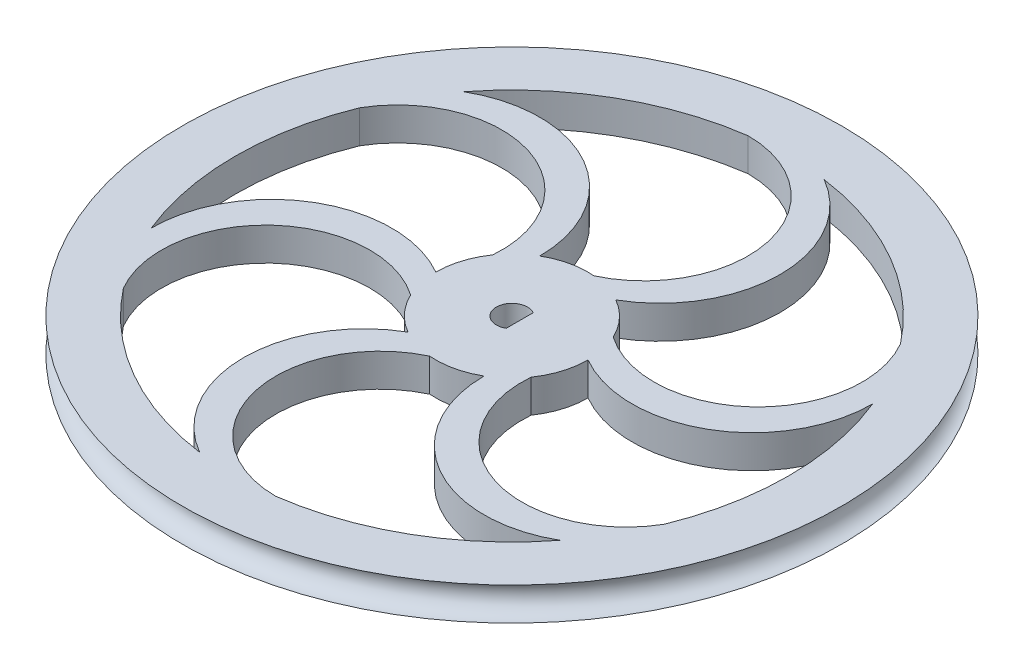
SolidWorks part; units mm, degrees
ref_plane "Front Plane" through (0, 0, 0) normal (0, 0, 1) x (1, 0, 0)
ref_plane "Top Plane" through (0, 0, 0) normal (0, 1, 0) x (1, 0, 0)
ref_plane "Right Plane" through (0, 0, 0) normal (1, 0, 0) x (0, 0, -1)
sketch "Sketch1" plane through (0, 0, 0) normal (0, 1, 0) x (1, 0, 0)
  circle A0 centre (0, 0) radius 31.75
  dimension "D1" = 63.5
extrude "Boss-Extrude1" add sketch "Sketch1" along normal blind 3.175
sketch "Sketch2" plane through (0, 0, 0) normal (0, 0, 1) x (1, 0, 0)
  line L0 (-31.75, 3.175) -> (-31.75, 0) construction
  line L1 (-31.75, 0) -> (0, 0) construction
  circle A0 centre (-31.75, 1.5875) radius 1.5875
  point P6 (-25.4, 1.7145)
  point P7 (0, 0)
  dimension "D1" = 3.175
ref_axis "Axis1" through (0, 0, 0) along (0, 1, 0)
revolve "Cut-Revolve1" cut sketch "Sketch2" angle 360 about axis through (0, 0, 0) along (0, 1, 0)
sketch "Sketch5" plane through (0, 3.175, 0) normal (0, 1, 0) x (1, 0, 0)
  line L0 (0, 0) -> (7.3323, 0) construction
  line L1 (7.3323, 0) -> (3.6662, 6.35)
  line L2 (3.6662, 6.35) -> (-3.6662, 6.35)
  line L3 (-3.6662, 6.35) -> (-7.3323, 0)
  line L4 (-7.3323, 0) -> (-3.6662, -6.35)
  line L5 (-3.6662, -6.35) -> (3.6662, -6.35)
  line L6 (3.6662, -6.35) -> (7.3323, 0)
  line L7 (0, 0) -> (-26.67, 0) construction
  line L8 (26.67, 0) -> (13.335, 23.0969)
  line L9 (13.335, 23.0969) -> (-13.335, 23.0969)
  line L10 (-13.335, 23.0969) -> (-26.67, 0)
  line L11 (-26.67, 0) -> (-13.335, -23.0969)
  line L12 (-13.335, -23.0969) -> (13.335, -23.0969)
  line L13 (13.335, -23.0969) -> (26.67, 0)
  line L14 (-3.6662, 6.35) -> (-3.6662, 26.4168) construction
  line L15 (3.6662, 6.35) -> (3.6662, 26.4168) construction
  line L16 (7.3323, 0) -> (24.7107, 10.0334) construction
  line L17 (3.6662, 6.35) -> (21.0445, 16.3834) construction
  line L18 (3.6662, -6.35) -> (21.0445, -16.3834) construction
  line L19 (7.3323, 0) -> (24.7107, -10.0334) construction
  line L20 (-3.6662, -6.35) -> (-3.6662, -26.4168) construction
  line L21 (3.6662, -6.35) -> (3.6662, -26.4168) construction
  line L22 (-7.3323, 0) -> (-24.7107, -10.0334) construction
  line L23 (-3.6662, -6.35) -> (-21.0445, -16.3834) construction
  line L24 (-3.6662, 6.35) -> (-21.0445, 16.3834) construction
  line L25 (-7.3323, 0) -> (-24.7107, 10.0334) construction
  line L26 (-26.67, 0) -> (-31.75, 0) construction
  circle A0 centre (0, 0) radius 6.35 construction
  circle A1 centre (0, 0) radius 23.0969 construction
  arc A3 (-3.6662, 6.35) -> (-3.6662, 26.4168) centre (-3.6662, 16.3834) ccw
  arc A4 (3.6662, 6.35) -> (3.6662, 26.4168) centre (-2.1266, 16.3834) ccw
  arc A5 (3.6662, 6.35) -> (21.0445, 16.3834) centre (12.3554, 11.3667) ccw
  arc A6 (7.3323, 0) -> (24.7107, 10.0334) centre (13.1251, 10.0334) ccw
  arc A7 (7.3323, 0) -> (24.7107, -10.0334) centre (16.0215, -5.0167) ccw
  arc A8 (3.6662, -6.35) -> (21.0445, -16.3834) centre (15.2518, -6.35) ccw
  arc A9 (3.6662, -6.35) -> (3.6662, -26.4168) centre (3.6662, -16.3834) ccw
  arc A10 (-3.6662, -6.35) -> (-3.6662, -26.4168) centre (2.1266, -16.3834) ccw
  arc A11 (-3.6662, -6.35) -> (-21.0445, -16.3834) centre (-12.3554, -11.3667) ccw
  arc A12 (-7.3323, 0) -> (-24.7107, -10.0334) centre (-13.1251, -10.0334) ccw
  arc A13 (-7.3323, 0) -> (-24.7107, 10.0334) centre (-16.0215, 5.0167) ccw
  arc A14 (-3.6662, 6.35) -> (-21.0445, 16.3834) centre (-15.2518, 6.35) ccw
  circle A15 centre (0, 0) radius 26.67
  circle A16 centre (0, 0) radius 31.75 construction
  point P53 (0, 0)
  dimension "D1" = 12.7
  dimension "D2" = 5.08
  dimension "D3" = 6
extrude "Cut-Extrude1" cut sketch "Sketch5" against normal through all contours A12 A13 L10 L11 | A10 A11 L11 L12 | A8 A9 L12 L13 | A6 A7 L13 L8 | A4 A5 L8 L9 | A14 A3 L9 L10 | L10 A15 A14 | A3 A15 L9 | L9 A15 A4 | A5 A15 L8 | L8 A15 A6 | L13 A15 A8 | A9 A15 L12 | L12 A15 A10 | A11 A15 L11 | L11 A15 A12 | A13 A15 L10 | A7 A15 L13
sketch "Sketch6" plane through (0, 3.175, 0) normal (0, 1, 0) x (1, 0, 0)
  circle A1 centre (0, 0) radius 7.3323
extrude "Boss-Extrude2" add sketch "Sketch6" against normal up to surface (3.175 mm away) up to face at (-18.8643, 0, -4.5686)
sketch "Sketch7" plane through (0, 3.175, 0) normal (0, 1, 0) x (1, 0, 0)
  line L0 (0.75, 1.299) -> (0.75, -1.299)
  line L1 (1.5, 0) -> (0.75, 1.299) construction
  line L2 (0.75, 1.299) -> (-0.75, 1.299) construction
  line L3 (-0.75, 1.299) -> (-1.5, 0) construction
  line L4 (-1.5, 0) -> (-0.75, -1.299) construction
  line L5 (-0.75, -1.299) -> (0.75, -1.299) construction
  line L6 (0.75, -1.299) -> (1.5, 0) construction
  line L7 (-1.5, 0) -> (1.5, 0) construction
  arc A0 (0.75, 1.299) -> (0.75, -1.299) centre (0, 0) ccw
  dimension "D1" = 3
extrude "Cut-Extrude2" cut sketch "Sketch7" against normal through all
